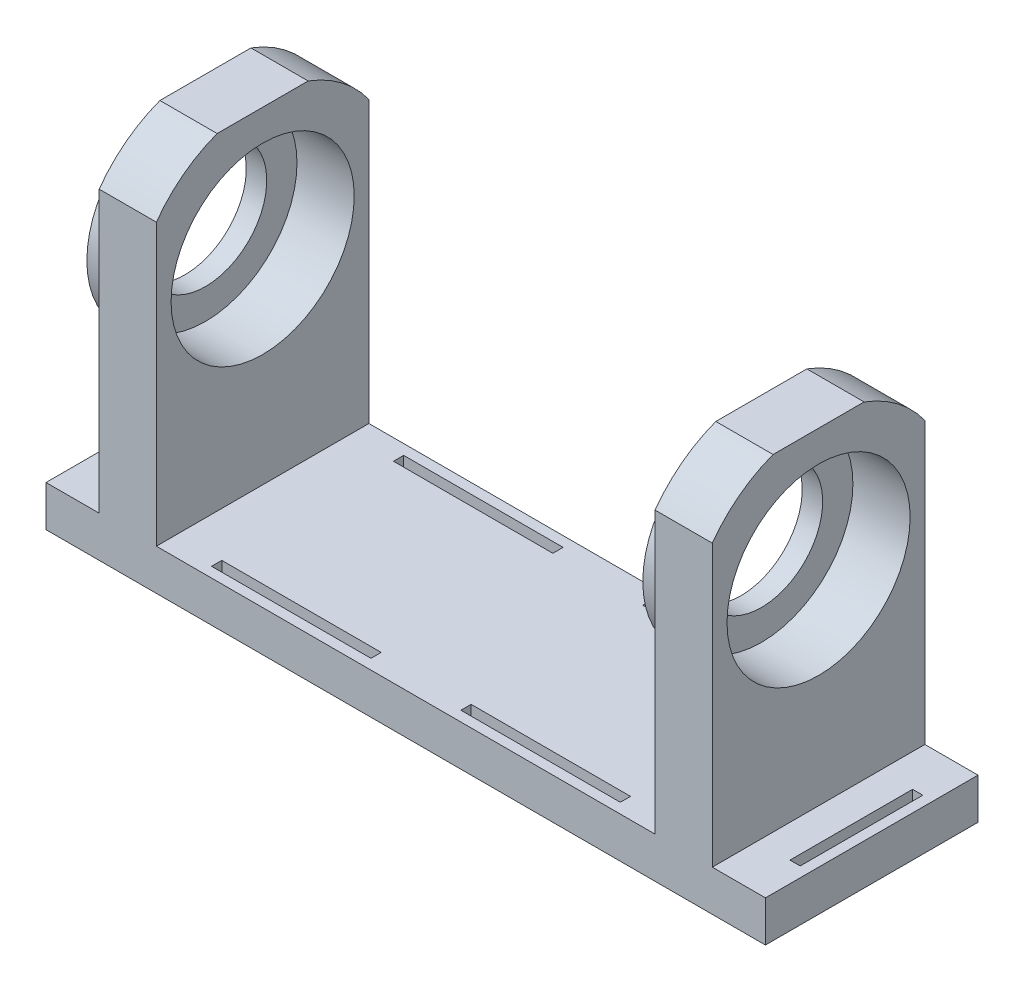
SolidWorks part; units mm, degrees
ref_plane "Front Plane" through (0, 0, 0) normal (0, 0, 1) x (1, 0, 0)
ref_plane "Top Plane" through (0, 0, 0) normal (0, 1, 0) x (1, 0, 0)
ref_plane "Right Plane" through (0, 0, 0) normal (1, 0, 0) x (0, 0, -1)
sketch "Sketch1" plane through (0, 0, 0) normal (0, 1, 0) x (1, 0, 0)
  line L0 (0, 0) -> (20, 0)
  line L1 (0, 0) -> (0, 26)
  line L2 (0, 26) -> (20, 26)
  line L3 (20, 26) -> (20, 0)
  line L4 (0, 26) -> (1.6662, 26)
  line L5 (2.5, 20.5) -> (2.5, 5.5)
  line L6 (20, 26) -> (16.6758, 26)
  line L8 (0, 26) -> (0.8331, 26)
  line L9 (1.25, 20.5) -> (1.25, 5.5)
  line L13 (0, 13) -> (20, 13) construction
  line L16 (2.5, 20.5) -> (1.25, 20.5)
  line L18 (2.5, 5.5) -> (1.25, 5.5)
  line L19 (10, 26) -> (10, 0) construction
  line L28 (14.1758, 26) -> (10, 26)
  dimension "D1" = 20
  dimension "D2" = 26
  dimension "D3" = 15
  dimension "D4" = 1.25
  dimension "D5" = 1.25
  dimension "D6" = 5.5
extrude "Boss-Extrude5" add sketch "Sketch1" along normal blind 5
sketch "Sketch3" plane through (0, 5, 0) normal (0, 1, 0) x (1, 0, 0)
  line L0 (2.5, 20.5) -> (2.5, 5.5) construction
  line L5 (6.5, 0) -> (13.5, 0)
  line L6 (6.5, 0) -> (6.5, 26)
  line L7 (6.5, 26) -> (13.5, 26)
  line L8 (13.5, 0) -> (13.5, 26)
  line L9 (6.5, 0) -> (13.5, 26) construction
  line L10 (6.5, 26) -> (13.5, 0) construction
  line L11 (0, 26) -> (20, 26) construction
  point P0 (10, 13)
  dimension "D1" = 7.5
  dimension "D2" = 7
  dimension "D3" = 26
  dimension "D4" = 13
extrude "Boss-Extrude6" add sketch "Sketch3" along normal blind 40
sketch "Sketch5" plane through (13.5, 0, 0) normal (1, 0, 0) x (0, 0, -1)
  line L0 (7.4322, 45) -> (0, 45)
  line L1 (26, 5) -> (0, 5) construction
  line L2 (13, 45) -> (13, 5) construction
  line L3 (0, 45) -> (26, 45) construction
  line L4 (0, 5) -> (26, 5) construction
  line L8 (0, 5) -> (26, 5)
  line L9 (26, 5) -> (26, 45)
  line L10 (26, 45) -> (0, 45)
  line L11 (0, 45) -> (0, 5)
  line L13 (26, 39.3274) -> (26, 45)
  line L14 (26, 45) -> (18.5678, 45)
  line L15 (0, 45) -> (0, 39.3274)
  circle A0 centre (13, 30) radius 11.2
  arc A1 (26, 39.3274) -> (18.5678, 45) centre (13, 30) ccw
  arc A2 (7.4322, 45) -> (0, 39.3274) centre (13, 30) ccw
  dimension "D1" = 32
  dimension "D2" = 22.4
  dimension "D3" = 25
  dimension "D4" = 0
extrude "Cut-Extrude1" cut sketch "Sketch5" against normal up to next
sketch "Sketch6" plane through (20, 0, 0) normal (1, 0, 0) x (0, 0, -1)
  line L1 (0, 0) -> (26, 0)
  line L2 (0, 0) -> (0, 5)
  line L3 (0, 5) -> (26, 5)
  line L4 (26, 0) -> (26, 5)
extrude "Boss-Extrude8" add sketch "Sketch6" along normal blind 24
mirror "Mirror5" about plane through (44, 0, 0) normal (-1, 0, 0) of "Cut-Extrude1", "Boss-Extrude8", "Boss-Extrude6", "Boss-Extrude5"
sketch "Sketch7" plane through (0, 5, 0) normal (0, 1, 0) x (1, 0, 0)
  line L0 (44, 26) -> (44, 0) construction
  line L1 (19, 1.25) -> (38.5, 1.25)
  line L2 (19, 1.25) -> (19, 2.5)
  line L3 (19, 2.5) -> (38.5, 2.5)
  line L4 (69, 1.25) -> (69, 2.5)
  line L5 (19, 2.5) -> (38.5, 1.25) construction
  line L6 (38.5, 2.5) -> (19, 1.25) construction
  line L7 (13.5, 26) -> (74.5, 26) construction
  line L8 (13.5, 0) -> (74.5, 0) construction
  line L9 (13.5, 0) -> (13.5, 26) construction
  line L10 (13.5, 13) -> (74.5, 13) construction
  line L11 (13.5, 7.4322) -> (13.5, 18.5678) construction
  line L12 (74.5, 7.4322) -> (74.5, 18.5678) construction
  line L13 (69, 23.5) -> (49.5, 24.75) construction
  line L14 (49.5, 23.5) -> (69, 24.75) construction
  line L19 (49.5, 2.5) -> (69, 2.5)
  line L21 (38.5, 2.5) -> (38.5, 1.25)
  line L23 (49.5, 2.5) -> (49.5, 1.25)
  line L24 (49.5, 2.5) -> (69, 1.25) construction
  line L25 (69, 2.5) -> (49.5, 1.25) construction
  line L26 (49.5, 1.25) -> (69, 1.25)
  line L27 (38.5, 23.5) -> (19, 24.75) construction
  line L28 (19, 23.5) -> (38.5, 24.75) construction
  line L29 (49.5, 24.75) -> (69, 24.75)
  line L30 (49.5, 23.5) -> (49.5, 24.75)
  line L31 (38.5, 23.5) -> (38.5, 24.75)
  line L32 (49.5, 23.5) -> (69, 23.5)
  line L33 (69, 24.75) -> (69, 23.5)
  line L34 (19, 23.5) -> (38.5, 23.5)
  line L35 (19, 24.75) -> (19, 23.5)
  line L36 (19, 24.75) -> (38.5, 24.75)
  point P0 (44, 1.875)
  point P24 (44, 1.875)
  point P29 (38.5, 1.875)
  point P30 (49.5, 1.875)
  point P31 (28.75, 1.875)
  point P32 (59.25, 1.875)
  point P33 (0, 0)
  point P37 (59.25, 24.125)
  point P38 (28.75, 24.125)
  point P39 (44, 24.125)
  dimension "D1" = 1.25
  dimension "D2" = 5.5
  dimension "D3" = 1.25
  dimension "D4" = 11
  dimension "D5" = 19.5
extrude "Cut-Extrude2" cut sketch "Sketch7" against normal up to next
sketch "Sketch8" plane through (6.5, 0, 0) normal (-1, 0, 0) x (0, 0, 1)
  circle A0 centre (-13, 30) radius 11.2 construction
  circle A3 centre (-13, 30) radius 12
  circle A4 centre (-13, 30) radius 7.5
  point P4 (-13, 30)
  dimension "D1" = 15
  dimension "D2" = 24
extrude "Boss-Extrude9" add sketch "Sketch8" along normal blind 2.5
sketch "Sketch9" plane through (74.5, 0, 0) normal (-1, 0, 0) x (0, 0, 1)
  circle A0 centre (-13, 30) radius 7.5 construction
  circle A1 centre (-13, 30) radius 12
  circle A2 centre (-13, 30) radius 12
  circle A3 centre (-13, 30) radius 7.5
  dimension "D1" = 0
extrude "Boss-Extrude10" add sketch "Sketch9" along normal blind 2.5
